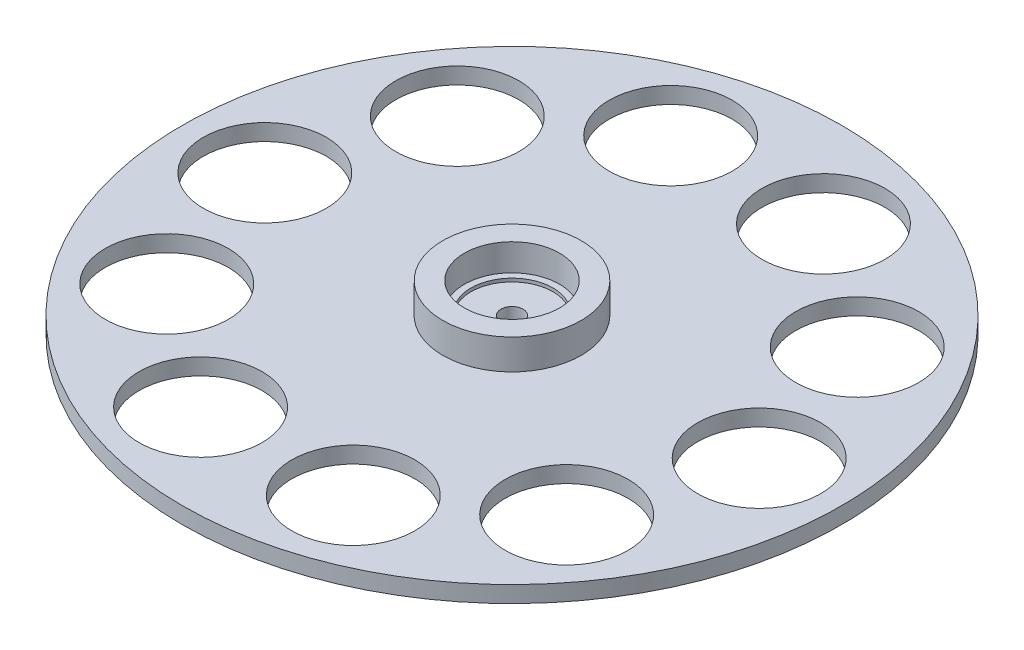
SolidWorks part; units mm, degrees
ref_plane "Front Plane" through (0, 0, 0) normal (0, 0, 1) x (1, 0, 0)
ref_plane "Top Plane" through (0, 0, 0) normal (0, 1, 0) x (1, 0, 0)
ref_plane "Right Plane" through (0, 0, 0) normal (1, 0, 0) x (0, 0, -1)
sketch "Sketch1" plane through (0, 0, 0) normal (0, 1, 0) x (1, 0, 0)
  circle A0 centre (-57.15, 0) radius 15.494 construction
  circle A1 centre (-46.2353, 33.5919) radius 15.494 construction
  circle A2 centre (-17.6603, 54.3529) radius 15.494 construction
  circle A3 centre (17.6603, 54.3529) radius 15.494 construction
  circle A4 centre (46.2353, 33.5919) radius 15.494 construction
  circle A5 centre (57.15, 0) radius 15.494 construction
  circle A6 centre (46.2353, -33.5919) radius 15.494 construction
  circle A7 centre (17.6603, -54.3529) radius 15.494 construction
  circle A8 centre (-17.6603, -54.3529) radius 15.494 construction
  circle A9 centre (0, 0) radius 76.2
  circle A10 centre (-57.15, 0) radius 14.224
  circle A11 centre (-46.2353, 33.5919) radius 14.224
  circle A12 centre (-17.6603, 54.3529) radius 14.224
  circle A13 centre (17.6603, 54.3529) radius 14.224
  circle A14 centre (46.2353, 33.5919) radius 14.224
  circle A15 centre (57.15, 0) radius 14.224
  circle A16 centre (46.2353, -33.5919) radius 14.224
  circle A17 centre (17.6603, -54.3529) radius 14.224
  circle A18 centre (-17.6603, -54.3529) radius 14.224
  circle A19 centre (-46.2353, -33.5919) radius 15.494 construction
  circle A20 centre (-46.2353, -33.5919) radius 14.224
  point P2 (0, 0)
  point P23 (0, 0)
  dimension "D1" = 30.988
  dimension "D2" = 57.15
  dimension "D3" = 10
  dimension "D4" = 28.448
  dimension "D5" = 152.4
extrude "Boss-Extrude1" add sketch "Sketch1" along normal blind 3.81
sketch "Sketch3" plane through (0, 3.81, 0) normal (0, 1, 0) x (1, 0, 0)
  circle A0 centre (0, 0) radius 35.56
  circle A1 centre (0, 0) radius 38.1
  dimension "D1" = 2.54
  dimension "D2" = 76.2
extrude "Boss-Extrude3" [suppressed] add sketch "Sketch3" along normal blind 7.62
sketch "Sketch2" [suppressed] plane through (0, 3.81, 0) normal (0, 1, 0) x (1, 0, 0)
  line L0 (0, 0) -> (-106.3551, -34.5569) construction
  line L1 (0, 0) -> (-57.15, 0) construction
  line L32 (-72.8529, -22.336) -> (-36.6076, -10.5592)
  line L33 (-72.068, -24.7517) -> (-35.8227, -12.9748)
  line L34 (-72.068, 24.7517) -> (-35.8227, 12.9748)
  line L35 (-72.8529, 22.336) -> (-36.6076, 10.5592)
  line L36 (-43.7556, 62.385) -> (-21.3547, 31.5529)
  line L37 (-45.8105, 60.892) -> (-23.4096, 30.0599)
  line L38 (1.27, 76.1894) -> (1.27, 38.0788)
  line L39 (-1.27, 76.1894) -> (-1.27, 38.0788)
  line L40 (45.8105, 60.892) -> (23.4096, 30.0599)
  line L41 (43.7556, 62.385) -> (21.3547, 31.5529)
  line L42 (72.8529, 22.336) -> (36.6076, 10.5592)
  line L43 (72.068, 24.7517) -> (35.8227, 12.9748)
  line L44 (72.068, -24.7517) -> (35.8227, -12.9748)
  line L45 (72.8529, -22.336) -> (36.6076, -10.5592)
  line L46 (43.7556, -62.385) -> (21.3547, -31.5529)
  line L47 (45.8105, -60.892) -> (23.4096, -30.0599)
  line L48 (-1.27, -76.1894) -> (-1.27, -38.0788)
  line L49 (1.27, -76.1894) -> (1.27, -38.0788)
  line L50 (-45.8105, -60.892) -> (-23.4096, -30.0599)
  line L51 (-43.7556, -62.385) -> (-21.3547, -31.5529)
  arc A0 (-36.6076, 10.5592) -> (-35.8227, 12.9748) centre (0, 0) cw
  arc A22 (-72.8529, 22.336) -> (-72.068, 24.7517) centre (0, 0) cw
  circle A23 centre (0, 0) radius 76.2 construction
  circle A24 centre (0, 0) radius 38.1 construction
  arc A25 (-35.8227, -12.9748) -> (-36.6076, -10.5592) centre (0, 0) cw
  arc A26 (-72.068, -24.7517) -> (-72.8529, -22.336) centre (0, 0) cw
  arc A27 (-23.4096, 30.0599) -> (-21.3547, 31.5529) centre (0, 0) cw
  arc A28 (-45.8105, 60.892) -> (-43.7556, 62.385) centre (0, 0) cw
  arc A29 (-1.27, 38.0788) -> (1.27, 38.0788) centre (0, 0) cw
  arc A30 (-1.27, 76.1894) -> (1.27, 76.1894) centre (0, 0) cw
  arc A31 (21.3547, 31.5529) -> (23.4096, 30.0599) centre (0, 0) cw
  arc A32 (43.7556, 62.385) -> (45.8105, 60.892) centre (0, 0) cw
  arc A33 (35.8227, 12.9748) -> (36.6076, 10.5592) centre (0, 0) cw
  arc A34 (72.068, 24.7517) -> (72.8529, 22.336) centre (0, 0) cw
  arc A35 (36.6076, -10.5592) -> (35.8227, -12.9748) centre (0, 0) cw
  arc A36 (72.8529, -22.336) -> (72.068, -24.7517) centre (0, 0) cw
  arc A37 (23.4096, -30.0599) -> (21.3547, -31.5529) centre (0, 0) cw
  arc A38 (45.8105, -60.892) -> (43.7556, -62.385) centre (0, 0) cw
  arc A39 (1.27, -38.0788) -> (-1.27, -38.0788) centre (0, 0) cw
  arc A40 (1.27, -76.1894) -> (-1.27, -76.1894) centre (0, 0) cw
  arc A41 (-21.3547, -31.5529) -> (-23.4096, -30.0599) centre (0, 0) cw
  arc A42 (-43.7556, -62.385) -> (-45.8105, -60.892) centre (0, 0) cw
  point P52 (0, 0)
  dimension "D2" = 2.54
  dimension "D1" = 18
  dimension "D3" = 10
extrude "Boss-Extrude4" [suppressed] add sketch "Sketch2" along normal up to surface (7.62 mm away)
sketch "Sketch4" plane through (0, 3.81, 0) normal (0, 1, 0) x (1, 0, 0)
  circle A0 centre (0, 0) radius 11
  circle A1 centre (0, 0) radius 16
  dimension "D1" = 5
  dimension "D2" = 22
extrude "Boss-Extrude5" add sketch "Sketch4" along normal blind 7
sketch "Sketch5" plane through (0, 3.81, 0) normal (0, 1, 0) x (1, 0, 0)
  circle A0 centre (0, 0) radius 11
  circle A1 centre (0, 0) radius 9.5
  dimension "D1" = 1.5
extrude "Boss-Extrude6" add sketch "Sketch5" along normal blind 0.762
sketch "Sketch6" plane through (0, 0, 0) normal (0, -1, 0) x (1, 0, 0)
  circle A0 centre (0, 0) radius 2.55
  dimension "D1" = 5.1
extrude "Cut-Extrude1" cut sketch "Sketch6" against normal through all
